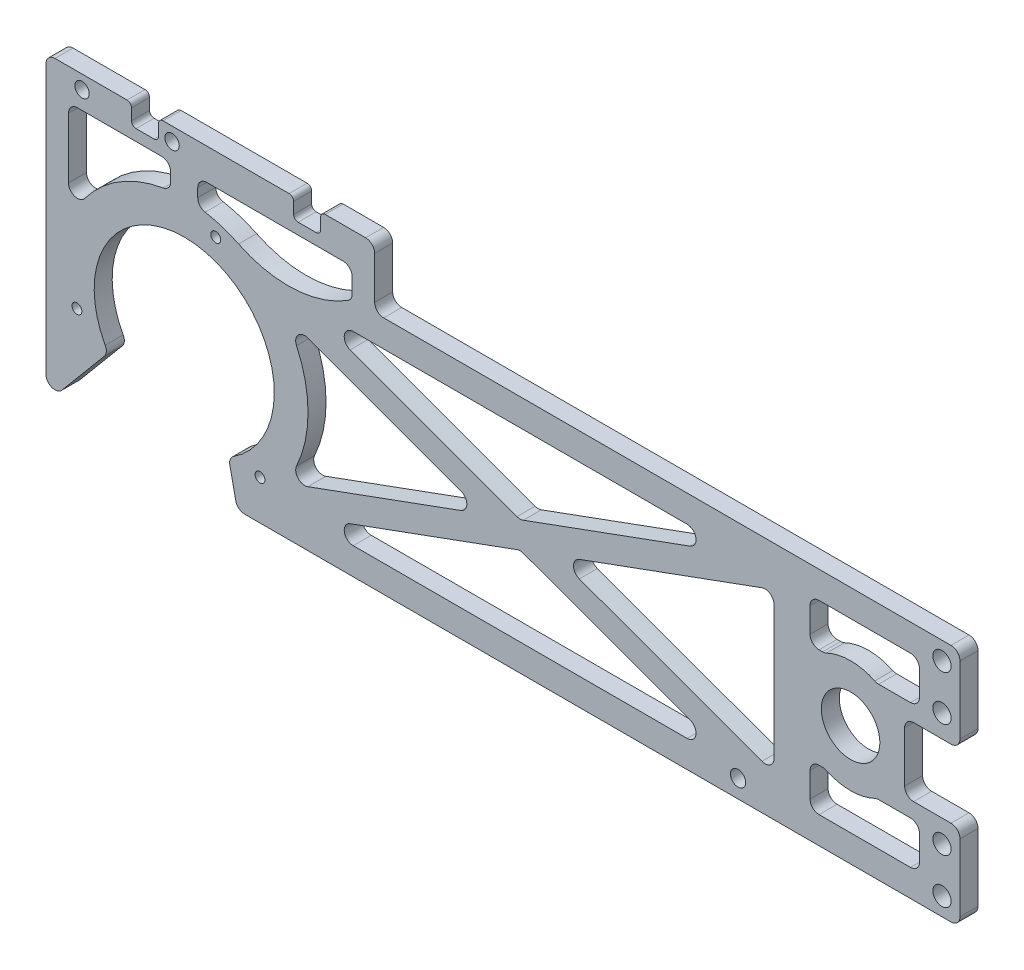
SolidWorks part; units mm, degrees
material "Thornel Mat VMA"
ref_plane "前视基准面" through (0, 0, 0) normal (0, 0, 1) x (1, 0, 0)
ref_plane "上视基准面" through (0, 0, 0) normal (0, 1, 0) x (1, 0, 0)
ref_plane "右视基准面" through (0, 0, 0) normal (1, 0, 0) x (0, 0, -1)
other "Configuration Table"
sketch "草图1" plane through (0, 0, 0) normal (0, 0, 1) x (1, 0, 0)
  line L1 (-175.7, 26.6) -> (24.3, 26.6)
  line L2 (-175.7, 26.6) -> (-175.7, -26.6)
  line L3 (-175.7, -26.6) -> (24.3, -26.6)
  line L4 (24.3, 26.6) -> (24.3, -26.6)
  circle A0 centre (0, 0) radius 6.5
  circle A1 centre (20.3, 22.6) radius 2.025
  circle A2 centre (20.3, 12.6) radius 2.025
  circle A3 centre (20.3, -12.6) radius 2.025
  circle A4 centre (20.3, -22.6) radius 2.025
  point P7 (24.3, 0)
  dimension "D1" = 4.05
  dimension "D7" = 13
  dimension "D2" = 24.3
  dimension "D3" = 4
  dimension "D4" = 10
  dimension "D5" = 10
  dimension "D6" = 25.2
  dimension "D8" = 12.6
  dimension "D9" = 4
  dimension "D10" = 200
extrude "凸台-拉伸1" add sketch "草图1" along normal mid plane 4
sketch "草图2" plane through (0, 0, 2) normal (0, 0, 1) x (1, 0, 0)
  circle A0 centre (-148, 0) radius 20
  dimension "D1" = 40
  dimension "D2" = 148
extrude "切除-拉伸1" cut sketch "草图2" against normal blind 5
sketch "草图3" plane through (0, 0, 2) normal (0, 0, 1) x (1, 0, 0)
  line L0 (-175.7, 26.6) -> (-175.7, -26.6) construction
  line L1 (-136.212, -26.6) -> (-139.2728, -12.1998)
  line L2 (-161.4331, -6.6746) -> (-175.7, -23.6772)
  line L4 (-175.7, -26.6) -> (24.3, -26.6) construction
  line L6 (-175.7, -26.6) -> (-136.212, -26.6)
  line L7 (-175.7, -23.6772) -> (-175.7, -26.6)
  arc A0 (-161.4331, -6.6746) -> (-139.2728, -12.1998) centre (-148, 0) ccw
  dimension "D1" = 30
extrude "切除-拉伸2" cut sketch "草图3" against normal blind 10
sketch "草图4" plane through (0, 0, 2) normal (0, 0, 1) x (1, 0, 0)
  circle A6 centre (-148, 0) radius 24.5 construction
  circle A7 centre (-141, 23.4787) radius 1.1
  circle A8 centre (-131.1668, -17.8015) radius 1.1
  circle A9 centre (-171.8332, -5.6772) radius 1.1
  circle A10 centre (-148, 0) radius 30 construction
  point P11 (-148, 0)
  dimension "D1" = 2.2
  dimension "D2" = 49
  dimension "D4" = 60
  dimension "D3" = 7
extrude "切除-拉伸3" cut sketch "草图4" against normal blind 10
sketch "草图5" plane through (0, 0, 2) normal (0, 0, 1) x (1, 0, 0)
  line L0 (-170.7, 37) -> (-150.7, 37) construction
  line L1 (-175.7, 26.6) -> (-105.7, 26.6)
  line L2 (-175.7, 26.6) -> (-175.7, 40)
  line L3 (-175.7, 40) -> (-105.7, 40)
  line L4 (-105.7, 26.6) -> (-105.7, 40)
  circle A0 centre (-148, 0) radius 28 construction
  circle A1 centre (-170.7, 37) radius 1.6
  circle A2 centre (-150.7, 37) radius 1.6
  dimension "D1" = 56
  dimension "D5" = 3.2
  dimension "D2" = 12
  dimension "D3" = 70
  dimension "D4" = 3
  dimension "D6" = 20
  dimension "D7" = 5
extrude "凸台-拉伸2" add sketch "草图5" against normal blind 4
sketch "草图6" plane through (0, 0, 2) normal (0, 0, 1) x (1, 0, 0)
  line L0 (-175.7, 40) -> (-178.7, 40)
  line L1 (-178.7, 40) -> (-178.7, -27.2525)
  line L2 (-178.7, -27.2525) -> (-175.7, -23.6772)
  line L3 (-175.7, -23.6772) -> (-175.7, 40)
  line L5 (-164.8599, -10.7585) -> (-175.7, -23.6772) construction
  dimension "D1" = 3
extrude "凸台-拉伸3" add sketch "草图6" against normal blind 4
sketch "草图7" plane through (0, 0, 2) normal (0, 0, 1) x (1, 0, 0)
  line L0 (24.3, -26.6) -> (24.3, 26.6) construction
  line L1 (24.3, -7.6) -> (12, -7.6)
  line L2 (24.3, -7.6) -> (24.3, 7.6)
  line L3 (24.3, 7.6) -> (12, 7.6)
  line L4 (12, -7.6) -> (12, 7.6)
  line L5 (0, 0) -> (-12.5, 0) construction
  line L6 (-9, -11.1) -> (15.3, -11.1)
  line L7 (-9, -11.1) -> (-9, -20.6)
  line L8 (-9, -20.6) -> (15.3, -20.6)
  line L9 (15.3, -11.1) -> (15.3, -20.6)
  line L10 (-136.212, -26.6) -> (24.3, -26.6) construction
  line L11 (-9, 20.6) -> (15.3, 20.6)
  line L12 (15.3, 11.1) -> (15.3, 20.6)
  line L13 (-9, 11.1) -> (15.3, 11.1)
  line L14 (-9, 11.1) -> (-9, 20.6)
  circle A0 centre (20.3, -12.6) radius 2.025 construction
  circle A1 centre (0, 0) radius 12.5
  circle A2 centre (20.3, -22.6) radius 2.025 construction
  point P6 (24.3, 0)
  line M16 (24.3, -26.6) -> (24.3, 26.6)
  dimension "D3" = 25
  dimension "D1" = 12
  dimension "D2" = 5
  dimension "D4" = 5
  dimension "D5" = 6
  dimension "D6" = 3.5
  dimension "D7" = 3.5
extrude "切除-拉伸4" cut sketch "草图7" against normal blind 10 contours A1 L4 L1 L3 M16 | A1 L6 L7 L8 L9 | A1 L13 L12 L11 L14 | L4 A1
sketch "草图8" plane through (0, 0, 2) normal (0, 0, 1) x (1, 0, 0)
  line L0 (-9, -20.6) -> (15.3, -20.6) construction
  line L1 (-17, -20.6) -> (-129.7822, -20.6)
  line L2 (-17, -20.6) -> (-17, 20.6)
  line L3 (-17, 20.6) -> (-129.7822, 20.6)
  line L5 (-9, 20.6) -> (15.3, 20.6) construction
  line L6 (-9, -11.1) -> (-9, -20.6) construction
  arc A0 (-129.7822, -20.6) -> (-129.7822, 20.6) centre (-148, 0) ccw
  dimension "D2" = 55
  dimension "D1" = 8
extrude "切除-拉伸5" cut sketch "草图8" against normal blind 10
sketch "草图9" plane through (0, 0, 2) normal (0, 0, 1) x (1, 0, 0)
  line L0 (-17, -20.6) -> (-129.7822, 20.6)
  line L1 (-17, 20.6) -> (-129.7822, -20.6)
extrude "拉伸-薄壁1" add sketch "草图9" against normal blind 4 thin thin type mid plane wall 5.5
sketch "草图10" plane through (0, 0, 2) normal (0, 0, 1) x (1, 0, 0)
  circle A0 centre (-131.1668, -17.8015) radius 1.1
extrude "切除-拉伸6" cut sketch "草图10" against normal blind 4
fillet "圆角1" radius 2 37 edges at (24.3, 26.6, 0) (-105.7, 26.6, 0) (-105.7, 40, 0) (-178.7, 40, 0) (-164.8599, -10.7585, 0) (-138.1644, -17.4144, 0) (-136.212, -26.6, 0) (24.3, -26.6, 0) (24.3, -7.6, 0) (12, -7.6, 0) (12, 7.6, 0) (24.3, 7.6, 0) (-178.7, -27.2525, 0) (-5.748, 11.1, 0) (5.748, 11.1, 0) (-9, 11.1, 0) (-9, 20.6, 0) (15.3, 20.6, 0) (15.3, 11.1, 0) (5.748, -11.1, 0) (-5.748, -11.1, 0) (15.3, -11.1, 0) (15.3, -20.6, 0) (-9, -20.6, 0) (-9, -11.1, 0) (-125.7877, 16.213, 0) (-81.4056, 0, 0) (-125.7877, -16.213, 0) (-25.0145, 20.6, 0) (-121.7676, -20.6, 0) (-121.7676, 20.6, 0) (-25.0145, -20.6, 0) (-65.3766, 0, 0) (-17, 17.6723, 0) (-17, -17.6723, 0) (-73.3911, 2.9277, 0) (-73.3911, -2.9277, 0)
sketch "草图11" plane through (0, 0, 2) normal (0, 0, 1) x (1, 0, 0)
  line L0 (-110.7, 26.6) -> (-110.7, 33)
  line L2 (-173.7, 33) -> (-151, 33)
  line L3 (-151, 33) -> (-151, 27.3359)
  line L4 (-110.7, 33) -> (-145, 33)
  line L5 (-145, 33) -> (-145, 27.3359)
  line L6 (-148, 0) -> (-148, 47.1479) construction
  line L7 (-105.7, 28.6) -> (-105.7, 38) construction
  line L8 (-173.7, 33) -> (-173.7, 9.7857)
  line L9 (-178.7, 38) -> (-178.7, -21.7575) construction
  arc A1 (-151, 27.3359) -> (-173.7, 9.7857) centre (-148, 0) ccw
  arc A2 (-135.9137, 24.7016) -> (-145, 27.3359) centre (-148, 0) ccw
  circle A3 centre (-170.7, 37) radius 1.6 construction
  arc A4 (-135.9137, 24.7016) -> (-110.7, 26.6) centre (-124.9261, 47.1577) ccw
  point P4 (-151, 30.1679)
  dimension "D1" = 6
  dimension "D4" = 50
  dimension "D2" = 5
  dimension "D3" = 4
  dimension "D5" = 5
extrude "切除-拉伸7" cut sketch "草图11" against normal blind 4
fillet "圆角2" radius 2 8 edges at (-145, 27.3359, 0) (-145, 33, 0) (-110.7, 33, 0) (-110.7, 26.6, 0) (-151, 33, 0) (-151, 27.3359, 0) (-173.7, 9.7857, 0) (-173.7, 33, 0)
sketch "草图12" plane through (0, 0, 2) normal (0, 0, 1) x (1, 0, 0)
  line L0 (-134.5924, -26.6) -> (22.3, -26.6) construction
  circle A0 centre (-25, -22.6) radius 1.55
  dimension "D1" = 3.1
  dimension "D2" = 4
  dimension "D3" = 25
extrude "切除-拉伸8" cut sketch "草图12" against normal blind 10
sketch "草图13" plane through (0, 0, -2) normal (0, 0, -1) x (-1, 0, 0)
  point P0 (25, -22.6)
hole_wizard "M3 锥坑平头螺钉的锥形沉头孔1" positions "草图13" profile "草图14" countersink size "M3" standard "ISO" end condition through all
sketch "草图14" plane through (-25, -22.6, -2) normal (1, 0, 0) x (0, 1, 0)
  line L0 (0, 0) -> (0, 4)
  line L1 (0, 4) -> (1.7, 4)
  line L2 (1.7, 4) -> (1.7, 1.45)
  line L3 (1.7, 1.45) -> (3.15, 0)
  line L5 (3.15, 0) -> (0, 0)
  line L6 (-1.7, 1.45) -> (-3.15, 0) construction
  line L11 (0, -6.35) -> (0, 107.95) construction
  dimension "通孔孔直径" = 3.4
  dimension "通孔孔深度" = 4
  dimension "近端锥形沉头孔直径" = 6.3
  dimension "近端锥形沉头孔角度" = 90
sketch "草图16" plane through (0, 0, 2) normal (0, 0, 1) x (1, 0, 0)
  line L0 (-107.7, 40) -> (-176.7, 40) construction
  line L1 (-123.7, 40) -> (-117.7, 40)
  line L2 (-123.7, 40) -> (-123.7, 35.5)
  line L3 (-123.7, 35.5) -> (-117.7, 35.5)
  line L4 (-117.7, 40) -> (-117.7, 35.5)
  line L5 (-120.7, 40) -> (-120.7, 45.3308) construction
  line L6 (-159.7, 40) -> (-153.7, 40)
  line L7 (-159.7, 40) -> (-159.7, 35.5)
  line L8 (-159.7, 35.5) -> (-153.7, 35.5)
  line L9 (-153.7, 40) -> (-153.7, 35.5)
  line L10 (-105.7, 28.6) -> (-105.7, 38) construction
  line L11 (-156.7, 40) -> (-156.7, 44.7181) construction
  line L12 (-178.7, 38) -> (-178.7, -21.7575) construction
  dimension "D1" = 15
  dimension "D2" = 6
  dimension "D3" = 4.5
  dimension "D4" = 22
extrude "切除-拉伸9" cut sketch "草图16" against normal blind 10
fillet "圆角3" radius 1 8 edges at (-153.7, 40, 0) (-159.7, 40, 0) (-117.7, 40, 0) (-123.7, 40, 0) (-117.7, 35.5, 0) (-123.7, 35.5, 0) (-153.7, 35.5, 0) (-159.7, 35.5, 0)
